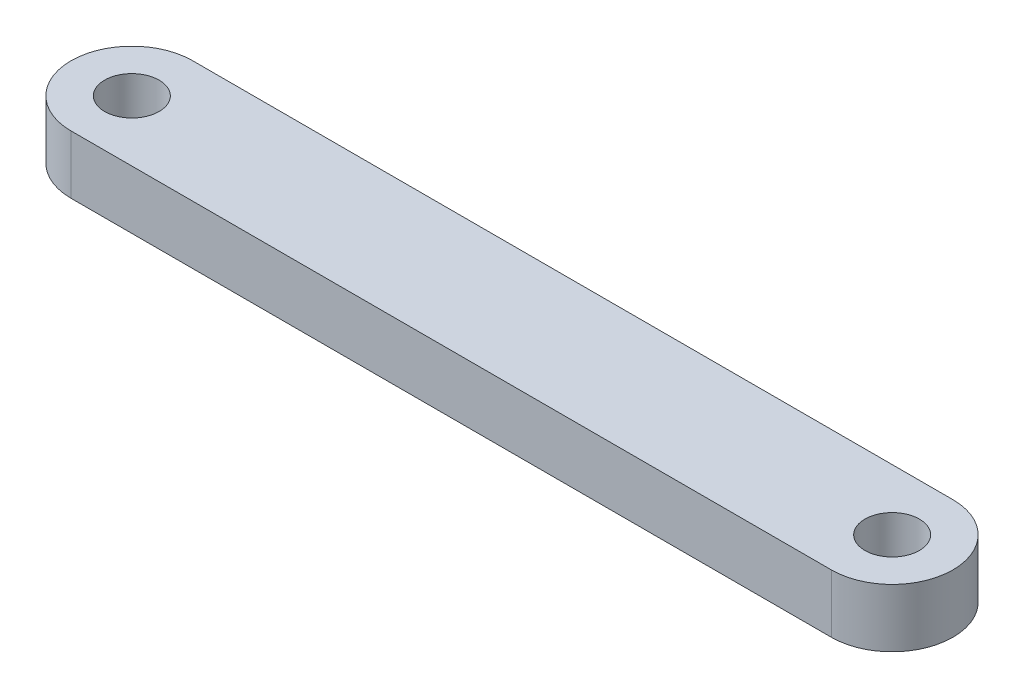
SolidWorks part; units mm, degrees
ref_plane "Front" through (0, 0, 0) normal (0, 0, 1) x (1, 0, 0)
ref_plane "Top" through (0, 0, 0) normal (0, 1, 0) x (1, 0, 0)
ref_plane "Right" through (0, 0, 0) normal (1, 0, 0) x (0, 0, -1)
sketch "Sketch1" plane through (0, 0, 0) normal (0, 1, 0) x (1, 0, 0)
  line L0 (-19.8501, 0) -> (19.8501, 0) construction
  line L1 (-19.8501, 3.175) -> (19.8501, 3.175)
  line L2 (-19.8501, -3.175) -> (19.8501, -3.175)
  arc A0 (-19.8501, 3.175) -> (-19.8501, -3.175) centre (-19.8501, 0) ccw
  arc A1 (19.8501, -3.175) -> (19.8501, 3.175) centre (19.8501, 0) ccw
  circle A2 centre (-19.8501, 0) radius 1.4224
  circle A3 centre (19.8501, 0) radius 1.4224
  point P2 (0, 0)
  dimension "D2" = 2.8448
  dimension "D1" = 39.7002
  dimension "D3" = 6.35
extrude "Boss-Extrude1" add sketch "Sketch1" along normal blind 3.048
